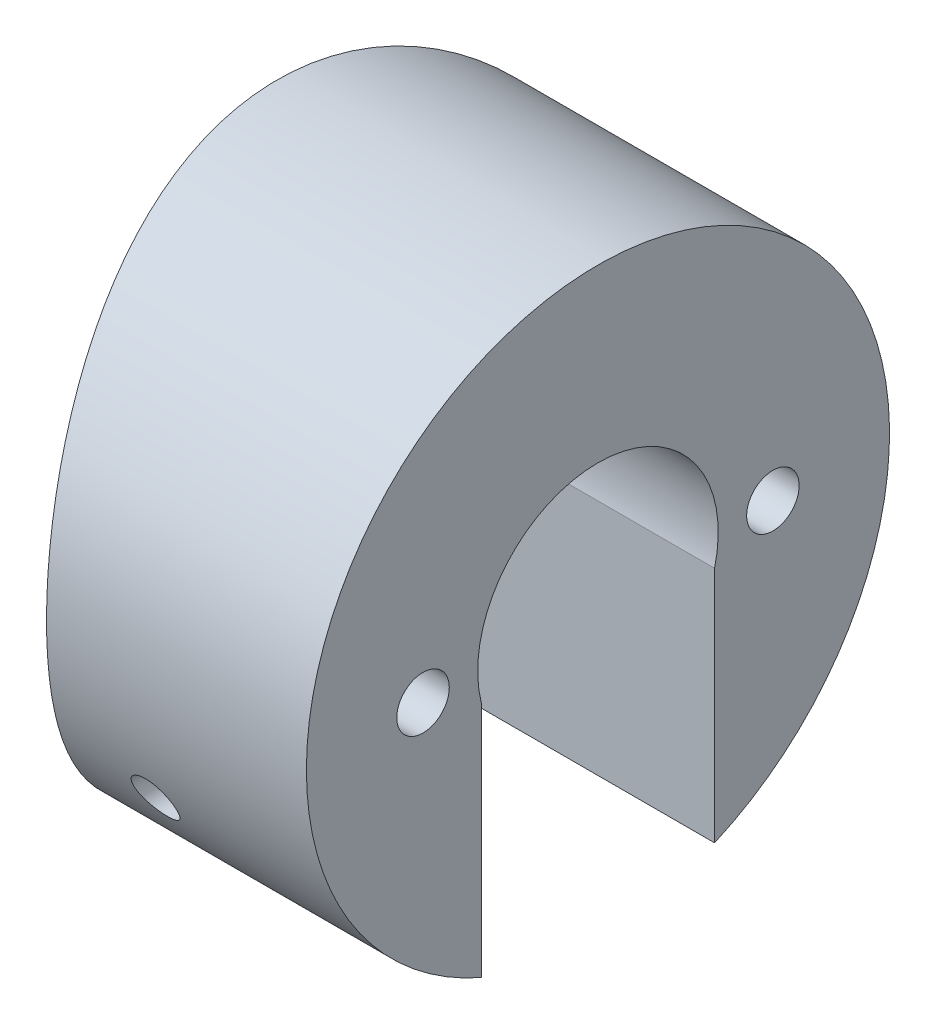
SolidWorks part; units mm, degrees
ref_plane "Plano frontal" through (0, 0, 0) normal (0, 0, 1) x (1, 0, 0)
ref_plane "Plano superior" through (0, 0, 0) normal (0, 1, 0) x (1, 0, 0)
ref_plane "Plano direito" through (0, 0, 0) normal (1, 0, 0) x (0, 0, -1)
sketch "Sketch1" plane through (0, 0, 0) normal (1, 0, 0) x (0, 0, -1)
  circle A0 centre (0, 0) radius 20
  dimension "D1" = 40
extrude "Boss-Extrude1" add sketch "Sketch1" along normal blind 22
sketch "Sketch2" plane through (22, 0, 0) normal (1, 0, 0) x (0, 0, -1)
  line L0 (-8, -18.3303) -> (-8, -2.0156)
  line L1 (8, -2.0156) -> (8, -18.3303)
  arc A0 (8, -2.0156) -> (-8, -2.0156) centre (0, 0) ccw
  circle A1 centre (0, 0) radius 20 construction
  arc A2 (-8, -18.3303) -> (8, -18.3303) centre (0, 0) ccw
  dimension "D1" = 16.5
  dimension "D2" = 8
  dimension "D3" = 16
extrude "Cut-Extrude1" cut sketch "Sketch2" against normal blind 19
hole_wizard "CSK for M3 SFHCS1" positions "Sketch5" profile "Sketch6" countersink size "M3" standard "ANSI Metric" end condition up to next
sketch "Sketch5" plane through (0, 0, 0) normal (-1, 0, 0) x (0, 0, 1)
  point P10 (-12, 0)
  point P12 (12, 0)
  dimension "D1" = 24
  dimension "D2" = 12
sketch "Sketch6" plane through (0, 0, -12) normal (0, 1, 0) x (0, 0, 1)
  line L0 (0, 0) -> (0, 22)
  line L1 (0, 22) -> (1.8, 22)
  line L2 (1.8, 22) -> (1.8, 1.56)
  line L3 (1.8, 1.56) -> (3.36, 0)
  line L5 (3.36, 0) -> (0, 0)
  line L6 (-1.8, 1.56) -> (-3.36, 0) construction
  line L11 (0, -6.35) -> (0, 107.95) construction
  dimension "Thru Hole Dia." = 3.6
  dimension "Thru Hole Depth" = 22
  dimension "Near C'Sink Dia." = 6.72
  dimension "Near C'Sink Angle" = 90
sketch "Sketch7" plane through (0, 0, 0) normal (0, 1, 0) x (1, 0, 0)
  circle A0 centre (50, 0) radius 50
  circle A1 centre (50, 0) radius 75
  dimension "D2" = 150
  dimension "D1" = 50
extrude "Cut-Extrude2" cut sketch "Sketch7" against normal up to next and the other way up to next
sketch "Sketch8" plane through (0, 0, 0) normal (0, 0, 1) x (1, 0, 0)
  line L0 (22, -18.3303) -> (22, 20) construction
  circle A0 centre (9.5, -9) radius 1.5
  dimension "D1" = 3
  dimension "D2" = 12.5
  dimension "D3" = 9
extrude "Cut-Extrude3" cut sketch "Sketch8" along normal up to next
